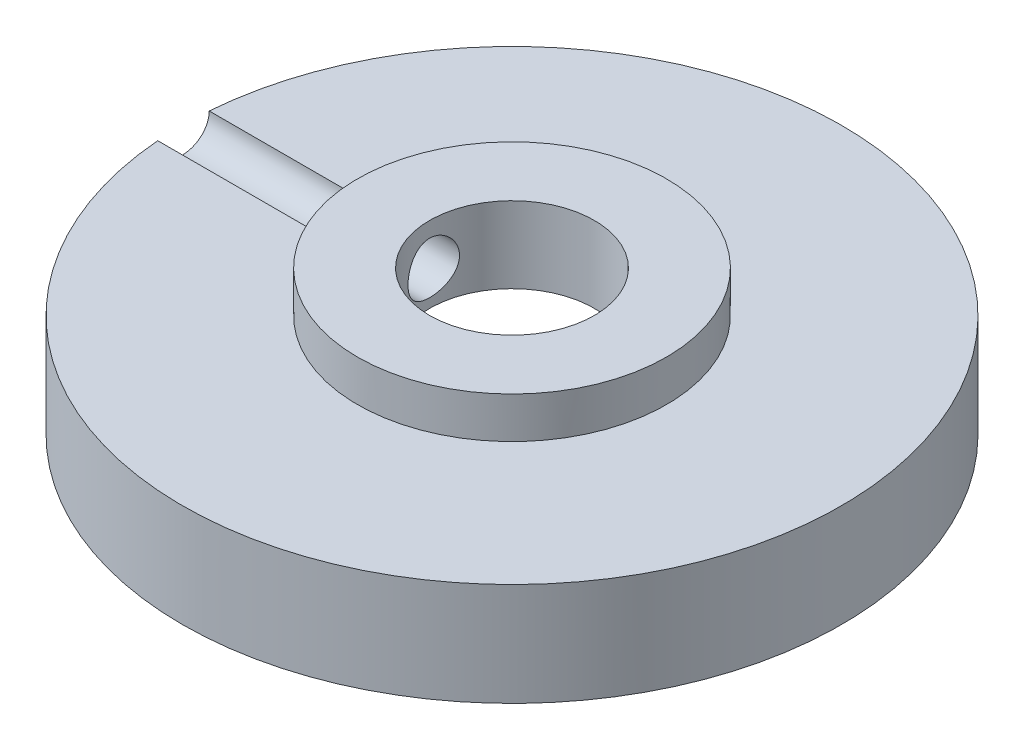
SolidWorks part; units mm, degrees
ref_plane "Front Plane" through (0, 0, 0) normal (0, 0, 1) x (1, 0, 0)
ref_plane "Top Plane" through (0, 0, 0) normal (0, 1, 0) x (1, 0, 0)
ref_plane "Right Plane" through (0, 0, 0) normal (1, 0, 0) x (0, 0, -1)
sketch "Sketch1" plane through (0, 0, 0) normal (0, 1, 0) x (1, 0, 0)
  line L0 (0, 0) -> (0, -10) construction
  line L1 (-1, -11.5) -> (1, -11.5)
  line L2 (-1, -11.5) -> (-1, -14.5)
  line L3 (-1, -14.5) -> (1, -14.5)
  line L4 (1, -11.5) -> (1, -14.5)
  line L5 (-1, -10) -> (1, -10)
  line L6 (-1, -10) -> (-1, -16)
  line L7 (-1, -16) -> (1, -16)
  line L8 (1, -10) -> (1, -16)
  line L9 (-3.0573, -9.5736) -> (-4.3047, -15.4424)
  line L10 (-3.0573, -9.5736) -> (-1.101, -9.9894)
  line L11 (-1.101, -9.9894) -> (-2.3484, -15.8583)
  line L12 (-4.3047, -15.4424) -> (-2.3484, -15.8583)
  line L13 (-3.9929, -13.9752) -> (-2.0366, -14.3911)
  line L14 (-3.3691, -11.0408) -> (-1.4128, -11.4566)
  line L15 (-4.9809, -8.7287) -> (-7.4213, -14.21)
  line L16 (-4.9809, -8.7287) -> (-3.1538, -9.5422)
  line L17 (-3.1538, -9.5422) -> (-5.5942, -15.0235)
  line L18 (-7.4213, -14.21) -> (-5.5942, -15.0235)
  line L19 (-6.8112, -12.8397) -> (-4.9841, -13.6531)
  line L20 (-5.591, -10.099) -> (-3.7639, -10.9125)
  line L21 (-6.6869, -7.5024) -> (-10.2136, -12.3565)
  line L22 (-6.6869, -7.5024) -> (-5.0688, -8.678)
  line L23 (-5.0688, -8.678) -> (-8.5955, -13.5321)
  line L24 (-10.2136, -12.3565) -> (-8.5955, -13.5321)
  line L25 (-9.3319, -11.143) -> (-7.7139, -12.3185)
  line L26 (-7.5685, -8.7159) -> (-5.9505, -9.8915)
  line L27 (-8.1006, -5.9482) -> (-12.5594, -9.9629)
  line L28 (-8.1006, -5.9482) -> (-6.7623, -7.4345)
  line L29 (-6.7623, -7.4345) -> (-11.2212, -11.4492)
  line L30 (-12.5594, -9.9629) -> (-11.2212, -11.4492)
  line L31 (-11.4447, -8.9592) -> (-10.1065, -10.4455)
  line L32 (-9.2153, -6.9519) -> (-7.877, -8.4381)
  line L33 (-9.1603, -4.134) -> (-14.3564, -7.134)
  line L34 (-9.1603, -4.134) -> (-8.1603, -5.866)
  line L35 (-8.1603, -5.866) -> (-13.3564, -8.866)
  line L36 (-14.3564, -7.134) -> (-13.3564, -8.866)
  line L37 (-13.0574, -6.384) -> (-12.0574, -8.116)
  line L38 (-10.4593, -4.884) -> (-9.4593, -6.616)
  line L39 (-9.8196, -2.1391) -> (-15.5259, -3.9932)
  line L40 (-9.8196, -2.1391) -> (-9.2015, -4.0412)
  line L41 (-9.2015, -4.0412) -> (-14.9079, -5.8953)
  line L42 (-15.5259, -3.9932) -> (-14.9079, -5.8953)
  line L43 (-14.0993, -3.5297) -> (-13.4813, -5.4318)
  line L44 (-11.2462, -2.6026) -> (-10.6281, -4.5048)
  line L45 (-10.0497, -0.0508) -> (-16.0169, -0.6779)
  line L46 (-10.0497, -0.0508) -> (-9.8407, -2.0398)
  line L47 (-9.8407, -2.0398) -> (-15.8078, -2.667)
  line L48 (-16.0169, -0.6779) -> (-15.8078, -2.667)
  line L49 (-14.5251, -0.5211) -> (-14.316, -2.5102)
  line L50 (-11.5415, -0.2076) -> (-11.3325, -2.1966)
  line L51 (-9.8407, 2.0398) -> (-15.8078, 2.667)
  line L52 (-9.8407, 2.0398) -> (-10.0497, 0.0508)
  line L53 (-10.0497, 0.0508) -> (-16.0169, 0.6779)
  line L54 (-15.8078, 2.667) -> (-16.0169, 0.6779)
  line L55 (-14.316, 2.5102) -> (-14.5251, 0.5211)
  line L56 (-11.3325, 2.1966) -> (-11.5415, 0.2076)
  line L57 (-9.2015, 4.0412) -> (-14.9079, 5.8953)
  line L58 (-9.2015, 4.0412) -> (-9.8196, 2.1391)
  line L59 (-9.8196, 2.1391) -> (-15.5259, 3.9932)
  line L60 (-14.9079, 5.8953) -> (-15.5259, 3.9932)
  line L61 (-13.4813, 5.4318) -> (-14.0993, 3.5297)
  line L62 (-10.6281, 4.5048) -> (-11.2462, 2.6026)
  line L63 (-8.1603, 5.866) -> (-13.3564, 8.866)
  line L64 (-8.1603, 5.866) -> (-9.1603, 4.134)
  line L65 (-9.1603, 4.134) -> (-14.3564, 7.134)
  line L66 (-13.3564, 8.866) -> (-14.3564, 7.134)
  line L67 (-12.0574, 8.116) -> (-13.0574, 6.384)
  line L68 (-9.4593, 6.616) -> (-10.4593, 4.884)
  line L69 (-6.7623, 7.4345) -> (-11.2212, 11.4492)
  line L70 (-6.7623, 7.4345) -> (-8.1006, 5.9482)
  line L71 (-8.1006, 5.9482) -> (-12.5594, 9.9629)
  line L72 (-11.2212, 11.4492) -> (-12.5594, 9.9629)
  line L73 (-10.1065, 10.4455) -> (-11.4447, 8.9592)
  line L74 (-7.877, 8.4381) -> (-9.2153, 6.9519)
  line L75 (-5.0688, 8.678) -> (-8.5955, 13.5321)
  line L76 (-5.0688, 8.678) -> (-6.6869, 7.5024)
  line L77 (-6.6869, 7.5024) -> (-10.2136, 12.3565)
  line L78 (-8.5955, 13.5321) -> (-10.2136, 12.3565)
  line L79 (-7.7139, 12.3185) -> (-9.3319, 11.143)
  line L80 (-5.9505, 9.8915) -> (-7.5685, 8.7159)
  line L81 (-3.1538, 9.5422) -> (-5.5942, 15.0235)
  line L82 (-3.1538, 9.5422) -> (-4.9809, 8.7287)
  line L83 (-4.9809, 8.7287) -> (-7.4213, 14.21)
  line L84 (-5.5942, 15.0235) -> (-7.4213, 14.21)
  line L85 (-4.9841, 13.6531) -> (-6.8112, 12.8397)
  line L86 (-3.7639, 10.9125) -> (-5.591, 10.099)
  line L87 (-1.101, 9.9894) -> (-2.3484, 15.8583)
  line L88 (-1.101, 9.9894) -> (-3.0573, 9.5736)
  line L89 (-3.0573, 9.5736) -> (-4.3047, 15.4424)
  line L90 (-2.3484, 15.8583) -> (-4.3047, 15.4424)
  line L91 (-2.0366, 14.3911) -> (-3.9929, 13.9752)
  line L92 (-1.4128, 11.4566) -> (-3.3691, 11.0408)
  line L93 (1, 10) -> (1, 16)
  line L94 (1, 10) -> (-1, 10)
  line L95 (-1, 10) -> (-1, 16)
  line L96 (1, 16) -> (-1, 16)
  line L97 (1, 14.5) -> (-1, 14.5)
  line L98 (1, 11.5) -> (-1, 11.5)
  line L99 (3.0573, 9.5736) -> (4.3047, 15.4424)
  line L100 (3.0573, 9.5736) -> (1.101, 9.9894)
  line L101 (1.101, 9.9894) -> (2.3484, 15.8583)
  line L102 (4.3047, 15.4424) -> (2.3484, 15.8583)
  line L103 (3.9929, 13.9752) -> (2.0366, 14.3911)
  line L104 (3.3691, 11.0408) -> (1.4128, 11.4566)
  line L105 (4.9809, 8.7287) -> (7.4213, 14.21)
  line L106 (4.9809, 8.7287) -> (3.1538, 9.5422)
  line L107 (3.1538, 9.5422) -> (5.5942, 15.0235)
  line L108 (7.4213, 14.21) -> (5.5942, 15.0235)
  line L109 (6.8112, 12.8397) -> (4.9841, 13.6531)
  line L110 (5.591, 10.099) -> (3.7639, 10.9125)
  line L111 (6.6869, 7.5024) -> (10.2136, 12.3565)
  line L112 (6.6869, 7.5024) -> (5.0688, 8.678)
  line L113 (5.0688, 8.678) -> (8.5955, 13.5321)
  line L114 (10.2136, 12.3565) -> (8.5955, 13.5321)
  line L115 (9.3319, 11.143) -> (7.7139, 12.3185)
  line L116 (7.5685, 8.7159) -> (5.9505, 9.8915)
  line L117 (8.1006, 5.9482) -> (12.5594, 9.9629)
  line L118 (8.1006, 5.9482) -> (6.7623, 7.4345)
  line L119 (6.7623, 7.4345) -> (11.2212, 11.4492)
  line L120 (12.5594, 9.9629) -> (11.2212, 11.4492)
  line L121 (11.4447, 8.9592) -> (10.1065, 10.4455)
  line L122 (9.2153, 6.9519) -> (7.877, 8.4381)
  line L123 (9.1603, 4.134) -> (14.3564, 7.134)
  line L124 (9.1603, 4.134) -> (8.1603, 5.866)
  line L125 (8.1603, 5.866) -> (13.3564, 8.866)
  line L126 (14.3564, 7.134) -> (13.3564, 8.866)
  line L127 (13.0574, 6.384) -> (12.0574, 8.116)
  line L128 (10.4593, 4.884) -> (9.4593, 6.616)
  line L129 (9.8196, 2.1391) -> (15.5259, 3.9932)
  line L130 (9.8196, 2.1391) -> (9.2015, 4.0412)
  line L131 (9.2015, 4.0412) -> (14.9079, 5.8953)
  line L132 (15.5259, 3.9932) -> (14.9079, 5.8953)
  line L133 (14.0993, 3.5297) -> (13.4813, 5.4318)
  line L134 (11.2462, 2.6026) -> (10.6281, 4.5048)
  line L135 (10.0497, 0.0508) -> (16.0169, 0.6779)
  line L136 (10.0497, 0.0508) -> (9.8407, 2.0398)
  line L137 (9.8407, 2.0398) -> (15.8078, 2.667)
  line L138 (16.0169, 0.6779) -> (15.8078, 2.667)
  line L139 (14.5251, 0.5211) -> (14.316, 2.5102)
  line L140 (11.5415, 0.2076) -> (11.3325, 2.1966)
  line L141 (9.8407, -2.0398) -> (15.8078, -2.667)
  line L142 (9.8407, -2.0398) -> (10.0497, -0.0508)
  line L143 (10.0497, -0.0508) -> (16.0169, -0.6779)
  line L144 (15.8078, -2.667) -> (16.0169, -0.6779)
  line L145 (14.316, -2.5102) -> (14.5251, -0.5211)
  line L146 (11.3325, -2.1966) -> (11.5415, -0.2076)
  line L147 (9.2015, -4.0412) -> (14.9079, -5.8953)
  line L148 (9.2015, -4.0412) -> (9.8196, -2.1391)
  line L149 (9.8196, -2.1391) -> (15.5259, -3.9932)
  line L150 (14.9079, -5.8953) -> (15.5259, -3.9932)
  line L151 (13.4813, -5.4318) -> (14.0993, -3.5297)
  line L152 (10.6281, -4.5048) -> (11.2462, -2.6026)
  line L153 (8.1603, -5.866) -> (13.3564, -8.866)
  line L154 (8.1603, -5.866) -> (9.1603, -4.134)
  line L155 (9.1603, -4.134) -> (14.3564, -7.134)
  line L156 (13.3564, -8.866) -> (14.3564, -7.134)
  line L157 (12.0574, -8.116) -> (13.0574, -6.384)
  line L158 (9.4593, -6.616) -> (10.4593, -4.884)
  line L159 (6.7623, -7.4345) -> (11.2212, -11.4492)
  line L160 (6.7623, -7.4345) -> (8.1006, -5.9482)
  line L161 (8.1006, -5.9482) -> (12.5594, -9.9629)
  line L162 (11.2212, -11.4492) -> (12.5594, -9.9629)
  line L163 (10.1065, -10.4455) -> (11.4447, -8.9592)
  line L164 (7.877, -8.4381) -> (9.2153, -6.9519)
  line L165 (5.0688, -8.678) -> (8.5955, -13.5321)
  line L166 (5.0688, -8.678) -> (6.6869, -7.5024)
  line L167 (6.6869, -7.5024) -> (10.2136, -12.3565)
  line L168 (8.5955, -13.5321) -> (10.2136, -12.3565)
  line L169 (7.7139, -12.3185) -> (9.3319, -11.143)
  line L170 (5.9505, -9.8915) -> (7.5685, -8.7159)
  line L171 (3.1538, -9.5422) -> (5.5942, -15.0235)
  line L172 (3.1538, -9.5422) -> (4.9809, -8.7287)
  line L173 (4.9809, -8.7287) -> (7.4213, -14.21)
  line L174 (5.5942, -15.0235) -> (7.4213, -14.21)
  line L175 (4.9841, -13.6531) -> (6.8112, -12.8397)
  line L176 (3.7639, -10.9125) -> (5.591, -10.099)
  line L177 (1.101, -9.9894) -> (2.3484, -15.8583)
  line L178 (1.101, -9.9894) -> (3.0573, -9.5736)
  line L179 (3.0573, -9.5736) -> (4.3047, -15.4424)
  line L180 (2.3484, -15.8583) -> (4.3047, -15.4424)
  line L181 (2.0366, -14.3911) -> (3.9929, -13.9752)
  line L182 (1.4128, -11.4566) -> (3.3691, -11.0408)
  circle A0 centre (0, 0) radius 10
  circle A1 centre (0, 0) radius 16
  point P11 (0, -10)
  point P248 (0, 0)
  dimension "D1" = 20
  dimension "D2" = 3
  dimension "D3" = 2
  dimension "D4" = 1.5
  dimension "D5" = 1.5
  dimension "D6" = 0
  dimension "D7" = 0
  dimension "D8" = 30
extrude "Boss-Extrude3" add sketch "Sketch1" along normal blind 1
sketch "Sketch2" plane through (0, 1, 0) normal (0, 1, 0) x (1, 0, 0)
  circle A0 centre (0, 0) radius 10 construction
  circle A1 centre (0, 0) radius 16 construction
  circle A2 centre (0, 0) radius 10
  circle A3 centre (0, 0) radius 16
extrude "Boss-Extrude4" add sketch "Sketch2" along normal blind 1.5
sketch "Sketch3" plane through (0, 2.5, 0) normal (0, 1, 0) x (1, 0, 0)
  circle A0 centre (0, 0) radius 10 construction
  circle A1 centre (0, 0) radius 16 construction
  circle A2 centre (0, 0) radius 10
  circle A3 centre (0, 0) radius 16
extrude "Boss-Extrude5" add sketch "Sketch3" along normal blind 0.8
sketch "Sketch4" plane through (0, 3.3, 0) normal (0, 1, 0) x (1, 0, 0)
  circle A0 centre (0, 0) radius 16 construction
  circle A1 centre (0, 0) radius 16
extrude "Boss-Extrude6" add sketch "Sketch4" along normal blind 1.7
sketch "Sketch5" plane through (0, 5, 0) normal (0, 1, 0) x (1, 0, 0)
  circle A0 centre (0, 0) radius 16 construction
  circle A1 centre (0, 0) radius 16
  circle A2 centre (0, 0) radius 4
  dimension "D1" = 8
extrude "Cut-Extrude3" cut sketch "Sketch5" against normal blind 1.7 contours A2
sketch "Sketch6" plane through (0, 5, 0) normal (0, 1, 0) x (1, 0, 0)
  circle A0 centre (0, 0) radius 4 construction
  circle A1 centre (0, 0) radius 4
  circle A2 centre (0, 0) radius 7.5
  dimension "D1" = 15
extrude "Boss-Extrude8" add sketch "Sketch6" along normal blind 2
sketch "Sketch8" plane through (0, 0, 0) normal (1, 0, 0) x (0, 0, -1)
  line L0 (7.5, 5) -> (-7.5, 5) construction
  line L1 (7.5, 7) -> (-7.5, 7) construction
  line L2 (7.5, 5) -> (-7.5, 5)
  line L3 (7.5, 7) -> (-7.5, 7)
  circle A0 centre (0, 5) radius 1.25
  dimension "D1" = 2.5
  dimension "D2" = 2
extrude "Cut-Extrude5" cut sketch "Sketch8" against normal blind 29 contours A0
